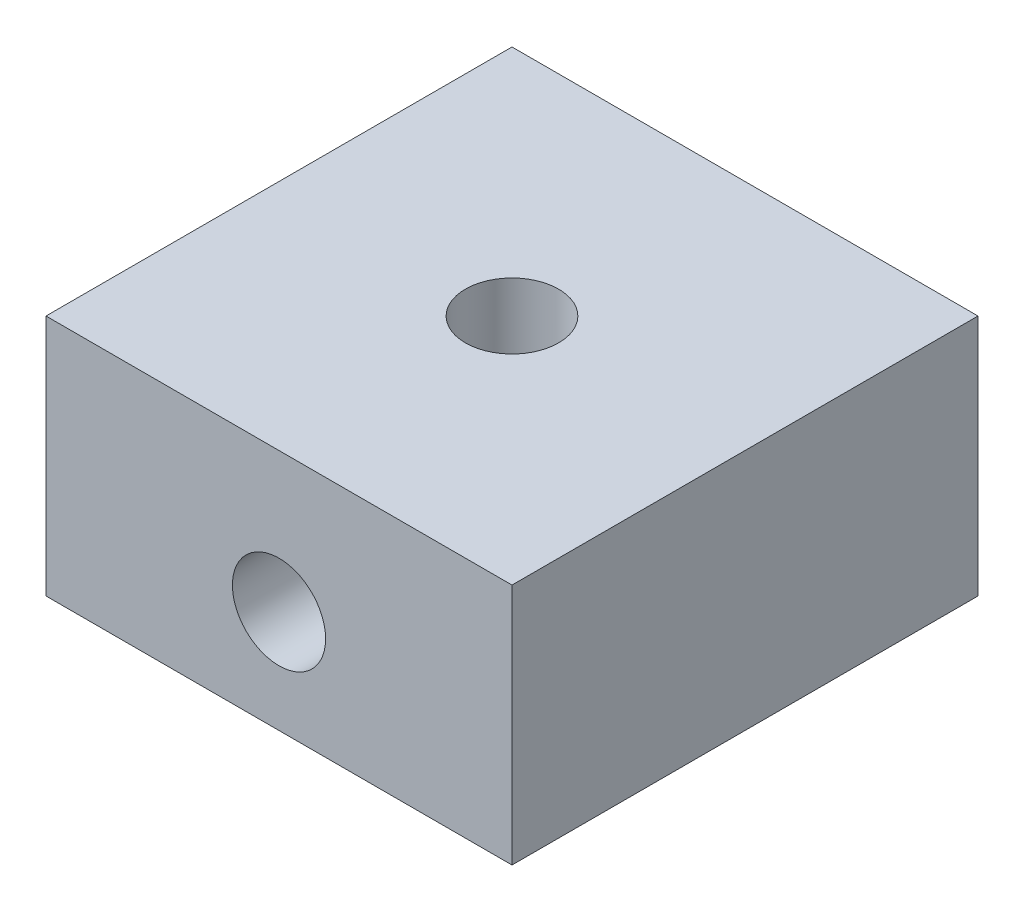
SolidWorks part; units mm, degrees
ref_plane "Front Plane" through (0, 0, 0) normal (0, 0, 1) x (1, 0, 0)
ref_plane "Top Plane" through (0, 0, 0) normal (0, 1, 0) x (1, 0, 0)
ref_plane "Right Plane" through (0, 0, 0) normal (1, 0, 0) x (0, 0, -1)
sketch "Sketch1" plane through (0, 0, 0) normal (0, 1, 0) x (1, 0, 0)
  line L1 (-25, 25) -> (25, 25)
  line L2 (-25, 25) -> (-25, -25)
  line L3 (-25, -25) -> (25, -25)
  line L4 (25, 25) -> (25, -25)
  line L5 (-25, 25) -> (25, -25) construction
  line L6 (-25, -25) -> (25, 25) construction
  point P0 (0, 0)
  dimension "D1" = 50
  dimension "D2" = 50
extrude "Boss-Extrude1" add sketch "Sketch1" along normal blind 25 and the other way blind 1.0186
ref_plane "Plane1" through (0, 25, 0) normal (0, 1, 0) x (1, 0, 0)
sketch "Sketch10" plane through (0, 0, 0) normal (0, 0, 1) x (1, 0, 0)
  line L1 (-5, 10) -> (5, 10)
  arc A0 (5, 10) -> (-5, 10) centre (0, 10) ccw
  point P7 (0, 10)
  dimension "D2" = 10
revolve "Cut-Revolve2" cut sketch "Sketch10" angle 360 about L1
sketch "Sketch11" plane through (0, 25, 0) normal (0, 1, 0) x (1, 0, 0)
  circle A0 centre (0, 0) radius 5
  dimension "D1" = 10
extrude "Cut-Extrude17" cut sketch "Sketch11" against normal blind 15
ref_plane "Plane3" through (0, 0, 25) normal (0, 0, 1) x (1, 0, 0)
sketch "Sketch14" plane through (0, 0, 25) normal (0, 0, 1) x (1, 0, 0)
  line L0 (0, 25) -> (0, 10) construction
  line L1 (27.5, 25) -> (-27.5, 25) construction
  circle A0 centre (0, 10) radius 5
  dimension "D2" = 10
  dimension "D1" = 15
extrude "Cut-Extrude18" cut sketch "Sketch14" against normal blind 25
